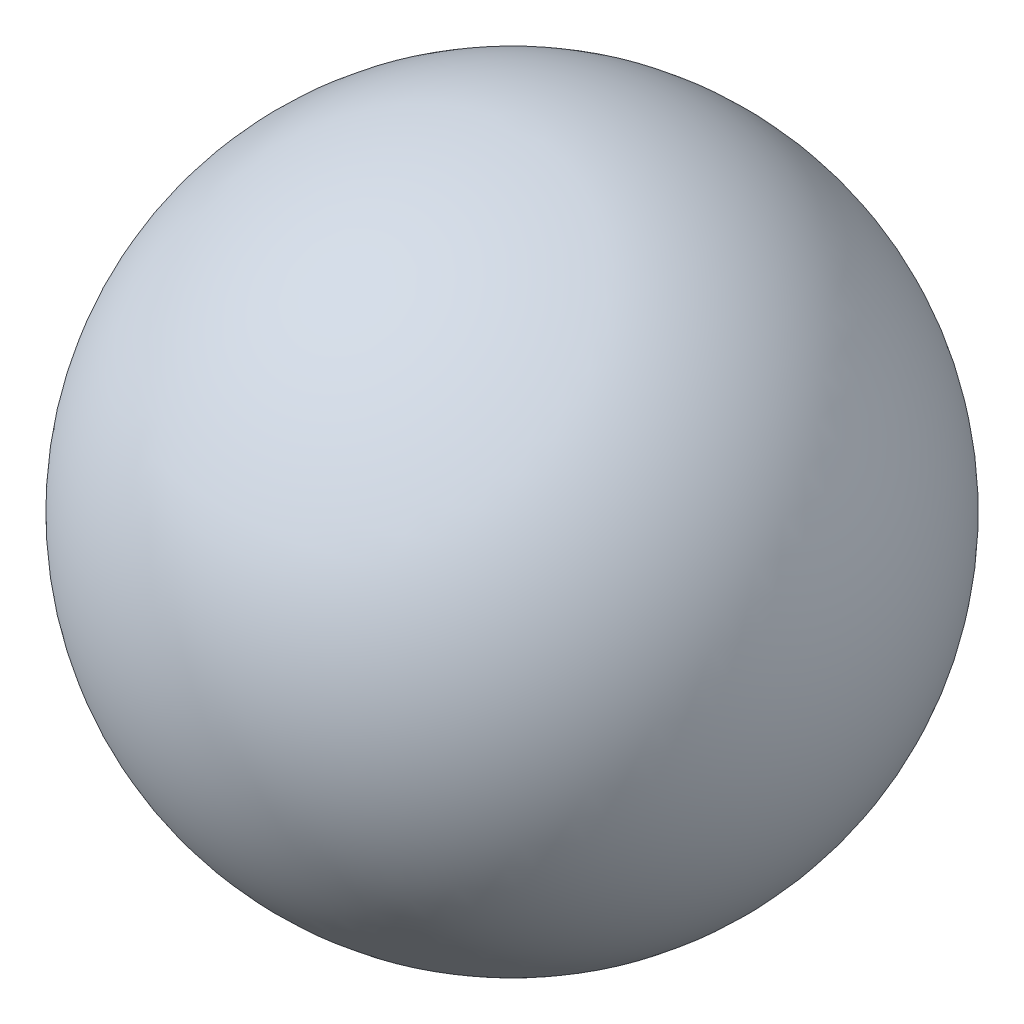
SolidWorks part; units mm, degrees
ref_plane "Front Plane" through (0, 0, 0) normal (0, 0, 1) x (1, 0, 0)
ref_plane "Top Plane" through (0, 0, 0) normal (0, 1, 0) x (1, 0, 0)
ref_plane "Right Plane" through (0, 0, 0) normal (1, 0, 0) x (0, 0, -1)
sketch "Sketch1" plane through (0, 0, 0) normal (0, 0, 1) x (1, 0, 0)
  line L0 (0, 127) -> (0, -127)
  arc A0 (0, 127) -> (0, -127) centre (0, 0) ccw
  dimension "D1" = 127
revolve "Revolve1" add sketch "Sketch1" angle 360 about L0
